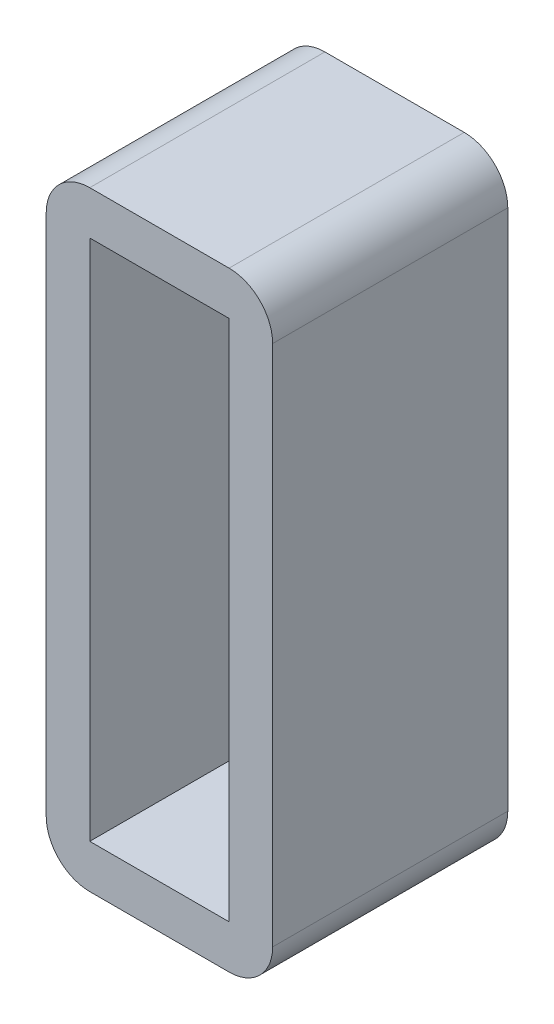
SolidWorks part; units mm, degrees
material "Copper"
ref_plane "Front Plane" through (0, 0, 0) normal (0, 0, 1) x (1, 0, 0)
ref_plane "Top Plane" through (0, 0, 0) normal (0, 1, 0) x (1, 0, 0)
ref_plane "Right Plane" through (0, 0, 0) normal (1, 0, 0) x (0, 0, -1)
sketch "Sketch1" plane through (0, 0, 0) normal (0, 0, 1) x (1, 0, 0)
  line L0 (-7.1526, 19.257) -> (11.2971, -30.4154) construction
  line L1 (-8, 30) -> (8, 30)
  line L2 (-8, 30) -> (-8, -30)
  line L3 (-8, -30) -> (8, -30)
  line L4 (8, 30) -> (8, -30)
  line L5 (-8, 30) -> (8, -30) construction
  line L6 (-8, -30) -> (8, 30) construction
  line L7 (-8, 35) -> (8, 35)
  line L8 (-13, 30) -> (-13, -30)
  line L9 (-8, -35) -> (8, -35)
  line L10 (13, 30) -> (13, -30)
  line L11 (-13, 35) -> (-12.1684, 32.7612) construction
  line L12 (-13, -35) -> (7.3868, 19.8876) construction
  line L13 (12.1684, 32.7612) -> (13, 35) construction
  line L14 (12.1684, -32.7612) -> (13, -35) construction
  arc A4 (-8, 35) -> (-13, 30) centre (-8, 30) ccw
  arc A5 (8, -35) -> (13, -30) centre (8, -30) ccw
  arc A6 (-13, -30) -> (-8, -35) centre (-8, -30) ccw
  arc A7 (8, 35) -> (13, 30) centre (8, 30) cw
  point P0 (0, 0)
  point P6 (0, 0)
  dimension "D6" = 5
  dimension "D7" = 5
  dimension "D8" = 5
  dimension "D9" = 5
  dimension "D1" = 60
  dimension "D2" = 16
  dimension "D3" = 26
  dimension "D4" = 70
extrude "Boss-Extrude1" add sketch "Sketch1" along normal mid plane 27
